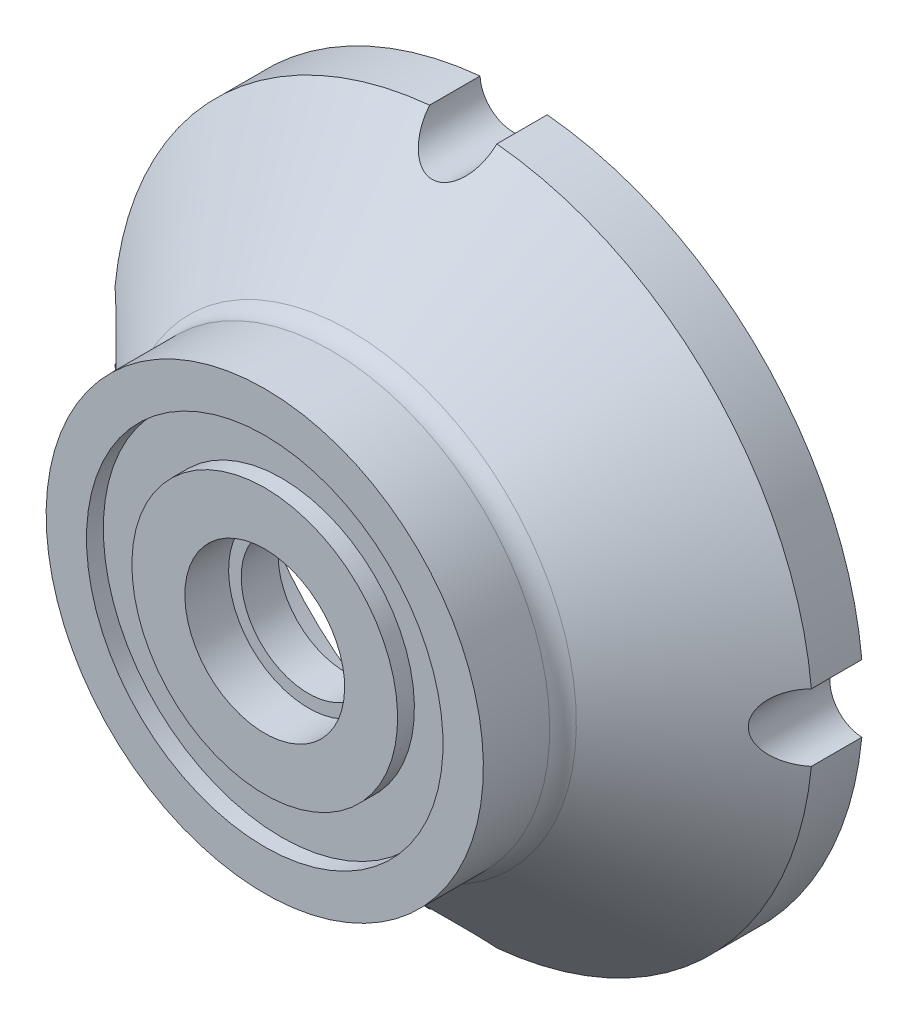
SolidWorks part; units mm, degrees
ref_plane "Front Plane" through (0, 0, 0) normal (0, 0, 1) x (1, 0, 0)
ref_plane "Top Plane" through (0, 0, 0) normal (0, 1, 0) x (1, 0, 0)
ref_plane "Right Plane" through (0, 0, 0) normal (1, 0, 0) x (0, 0, -1)
sketch "Sketch2" plane through (0, 0, 0) normal (1, 0, 0) x (0, 0, -1)
  line L0 (0, 0) -> (-21.2, 0) construction
  line L1 (0, 17) -> (0, 20.8)
  line L2 (0, 20.8) -> (-3, 20.8)
  line L3 (-3, 20.8) -> (-10.2, 13)
  line L4 (-10.2, 13) -> (-14.8, 13)
  line L5 (-14.8, 13) -> (-14.8, 10.6)
  line L6 (-14.8, 10.6) -> (-13.8, 10.6)
  line L7 (-13.8, 10.6) -> (-13.8, 7.9)
  line L8 (-13.8, 7.9) -> (-14.8, 7.9)
  line L9 (-14.8, 7.9) -> (-14.8, 4.75)
  line L10 (-14.8, 4.75) -> (-12.2, 4.75)
  line L11 (-12.2, 4.75) -> (-12.2, 4)
  line L12 (-12.2, 4) -> (-10, 4)
  line L13 (-10, 4) -> (-10, 11.2)
  line L14 (-10, 11.2) -> (-4.2, 17)
  line L15 (-4.2, 17) -> (0, 17)
  dimension "D1" = 41.6
  dimension "D2" = 14.8
  dimension "D3" = 26
  dimension "D4" = 9.5
  dimension "D5" = 8
  dimension "D6" = 1
  dimension "D7" = 15.8
  dimension "D8" = 21.2
  dimension "D9" = 10
  dimension "D10" = 22.4
  dimension "D11" = 2.6
  dimension "D12" = 3.8
  dimension "D13" = 3
  dimension "D14" = 10.2
  dimension "D15" = 4.2
revolve "Revolve1" add sketch "Sketch2" angle 360 about L0
sketch "Sketch3" plane through (0, 0, 0) normal (0, 0, 1) x (1, 0, 0)
  circle A0 centre (0, 20.8) radius 2
  circle A1 centre (0, 0) radius 20.8 construction
  circle A2 centre (20.8, 0) radius 2
  circle A3 centre (0, -20.8) radius 2
  circle A4 centre (-20.8, 0) radius 2
  dimension "D1" = 4
  dimension "D2" = 4
extrude "Cut-Extrude1" cut sketch "Sketch3" along normal up to next
fillet "Fillet1" radius 1.5 1 edges at (0, 13, 10.2)
